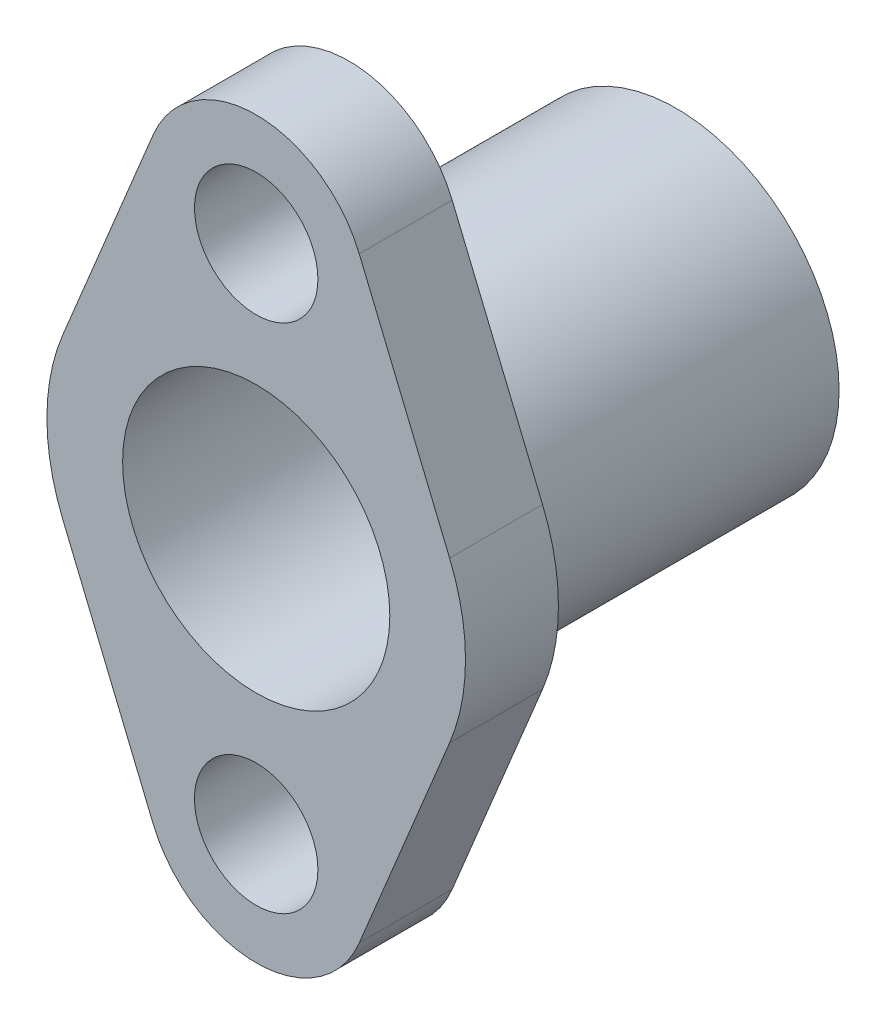
SolidWorks part; units mm, degrees
ref_plane "Front Plane" through (0, 0, 0) normal (0, 0, 1) x (1, 0, 0)
ref_plane "Top Plane" through (0, 0, 0) normal (0, 1, 0) x (1, 0, 0)
ref_plane "Right Plane" through (0, 0, 0) normal (1, 0, 0) x (0, 0, -1)
sketch "Sketch1" plane through (0, 0, 0) normal (1, 0, 0) x (0, 0, -1)
  line L0 (-0.254, 5.5626) -> (10.922, 5.5626)
  line L1 (10.922, 5.5626) -> (10.922, 4.2494)
  line L2 (10.922, 4.2494) -> (9.906, 4.2494)
  line L3 (9.906, 4.2494) -> (9.7242, 4.5644)
  line L4 (9.7242, 4.5644) -> (-3.429, 4.5644)
  line L5 (-3.429, 4.5644) -> (-3.429, 12.7)
  line L6 (-3.429, 12.7) -> (-0.254, 12.7)
  line L7 (-0.254, 12.7) -> (-0.254, 5.5626)
  line L8 (8.4718, 0) -> (21.4116, 0) construction
  dimension "D1" = 60
  dimension "D2" = 1.016
  dimension "D3" = 11.176
  dimension "D4" = 3.175
  dimension "D5" = 0.254
  dimension "D6" = 8.4988
  dimension "D7" = 9.1288
  dimension "D8" = 11.1252
  dimension "D9" = 25.4
revolve "Revolve1" add sketch "Sketch1" angle 360 about L8
sketch "Sketch2" plane through (0, 0, 0) normal (0, 0, 1) x (1, 0, 0)
  line L0 (11.9686, 0) -> (17.3188, 0) construction
  line L1 (6.6071, 2.7333) -> (3.5206, 10.194)
  line L2 (-3.5206, 10.194) -> (-6.6071, 2.7333)
  line L3 (-6.6071, -2.7333) -> (-3.5206, -10.194)
  line L4 (3.5206, -10.194) -> (6.6071, -2.7333)
  arc A0 (3.5206, 10.194) -> (-3.5206, 10.194) centre (0, 8.7376) ccw
  arc A1 (-6.6071, 2.7333) -> (-6.6071, -2.7333) centre (0, 0) ccw
  arc A2 (-3.5206, -10.194) -> (3.5206, -10.194) centre (0, -8.7376) ccw
  arc A3 (6.6071, -2.7333) -> (6.6071, 2.7333) centre (0, 0) ccw
  circle A4 centre (0, 8.7376) radius 2.1082
  circle A5 centre (0, -8.7376) radius 2.1082
  circle A6 centre (-2.7725, 7.2903) radius 1.5875 construction
  circle A7 centre (-2.7725, 7.2903) radius 3.048 construction
  dimension "D1" = 14.3002
  dimension "D2" = 3.81
  dimension "D3" = 4.2164
  dimension "D4" = 8.7376
  dimension "D5" = 8.7376
  dimension "D6" = 25.0952
  dimension "D7" = 3.175
  dimension "D8" = 6.096
extrude "Cut-Extrude1" cut sketch "Sketch2" along normal through all flip side to cut
